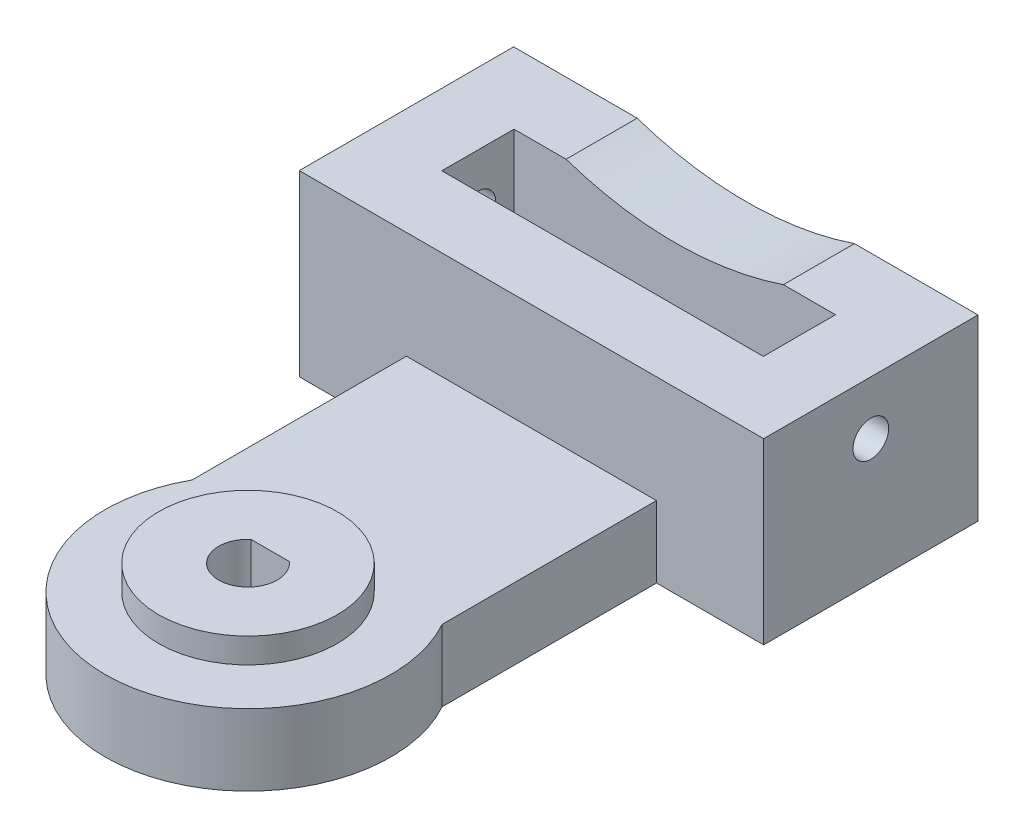
SolidWorks part; units mm, degrees
ref_plane "Front Plane" through (0, 0, 0) normal (0, 0, 1) x (1, 0, 0)
ref_plane "Top Plane" through (0, 0, 0) normal (0, 1, 0) x (1, 0, 0)
ref_plane "Right Plane" through (0, 0, 0) normal (1, 0, 0) x (0, 0, -1)
sketch "Sketch1" plane through (0, 0, 0) normal (0, 1, 0) x (1, 0, 0)
  circle A21 centre (0, 0) radius 20
  dimension "D1" = 40
extrude "Boss-Extrude1" add sketch "Sketch1" along normal blind 10
sketch "Sketch2" plane through (0, 10, 0) normal (0, 1, 0) x (1, 0, 0)
  line L0 (-2.6458, 3) -> (2.6458, 3) construction
  line L1 (-2.6833, 3.1) -> (2.6833, 3.1)
  arc A0 (-2.6458, 3) -> (2.6458, 3) centre (0, 0) ccw construction
  arc A1 (-2.6833, 3.1) -> (2.6833, 3.1) centre (0, 0) ccw
  point P3 (0, 3)
  dimension "D1" = 4
  dimension "D2" = 5.2915
  dimension "D3" = 0.1
extrude "Cut-Extrude1" cut sketch "Sketch2" against normal offset from surface (2.5 mm away) 7.5 up to face at (0, 0, 20)
sketch "Sketch3" plane through (0, 0, 0) normal (0, 1, 0) x (1, 0, 0)
  line L0 (-17.5, 59.6825) -> (-17.5, 9.6825)
  line L1 (-17.5, 59.6825) -> (17.5, 59.6825)
  line L2 (17.5, 59.6825) -> (17.5, 9.6825)
  circle A0 centre (0, 0) radius 20 construction
  arc A1 (17.5, 9.6825) -> (-17.5, 9.6825) centre (0, 0) ccw
  point P6 (0, 59.6825)
  point P9 (0, 20)
  dimension "D1" = 35
  dimension "D2" = 50
extrude "Boss-Extrude2" add sketch "Sketch3" along normal up to surface (10 mm away) up to face at (0, 10, 0.5)
sketch "Sketch6" plane through (0, 10, 0) normal (0, 1, 0) x (1, 0, 0)
  line L5 (-2.6833, 3.1) -> (2.6833, 3.1) construction
  line L6 (-2.6833, 3.1) -> (2.6833, 3.1)
  circle A0 centre (0, 0) radius 12.5
  arc A3 (-2.6833, 3.1) -> (2.6833, 3.1) centre (0, 0) ccw construction
  arc A4 (-2.6833, 3.1) -> (2.6833, 3.1) centre (0, 0) ccw
  dimension "D1" = 25
extrude "Boss-Extrude3" add sketch "Sketch6" along normal blind 6
sketch "Sketch7" plane through (0, 0, -59.6825) normal (0, 0, -1) x (-1, 0, 0)
  line L0 (-32.5, 0) -> (-32.5, 25)
  line L1 (-32.5, 25) -> (-22.5, 25)
  line L2 (-22.5, 25) -> (-22.5, 10)
  line L3 (-17.5, 10) -> (17.5, 10) construction
  line L4 (-22.5, 10) -> (22.5, 10)
  line L5 (22.5, 10) -> (22.5, 25)
  line L6 (22.5, 25) -> (32.5, 25)
  line L7 (32.5, 25) -> (32.5, 0)
  line L8 (32.5, 0) -> (-32.5, 0)
  dimension "D1" = 10
  dimension "D2" = 15
  dimension "D3" = 45
extrude "Boss-Extrude4" add sketch "Sketch7" against normal blind 20 and the other way blind 10
sketch "Sketch8" plane through (-32.5, 0, 0) normal (-1, 0, 0) x (0, 0, 1)
  line L1 (-39.6825, 25) -> (-69.6825, 25) construction
  circle A0 centre (-54.6825, 17.5) radius 2.5
  point P7 (-54.6825, 25)
  dimension "D2" = 5
  dimension "D1" = 7.5
extrude "Cut-Extrude2" cut sketch "Sketch8" against normal through all
sketch "Sketch9" plane through (0, 16, 0) normal (0, 1, 0) x (1, 0, 0)
  circle A0 centre (0, 0) radius 12.5
  circle A1 centre (0, 0) radius 12.5 construction
extrude "Cut-Extrude3" cut sketch "Sketch9" against normal blind 2.5
sketch "Sketch10" plane through (0, 0, -69.6825) normal (0, 0, -1) x (-1, 0, 0)
  line L1 (-22.5, 10) -> (22.5, 10)
  line L2 (-22.5, 10) -> (-22.5, 25)
  line L3 (-22.5, 25) -> (22.5, 25)
  line L4 (22.5, 10) -> (22.5, 25)
extrude "Boss-Extrude5" add sketch "Sketch10" against normal blind 9.95
sketch "Sketch11" plane through (0, 0, -39.6825) normal (0, 0, 1) x (1, 0, 0)
  line L1 (-22.5, 10) -> (22.5, 10)
  line L2 (-22.5, 10) -> (-22.5, 25)
  line L3 (-22.5, 25) -> (22.5, 25)
  line L4 (22.5, 10) -> (22.5, 25)
extrude "Boss-Extrude6" add sketch "Sketch11" against normal blind 9.95
sketch "Sketch12" plane through (0, 0, -69.6825) normal (0, 0, -1) x (-1, 0, 0)
  circle A0 centre (0, 70) radius 47.5
  dimension "D1" = 95
  dimension "D2" = 70
extrude "Cut-Extrude5" cut sketch "Sketch12" against normal blind 9.95
